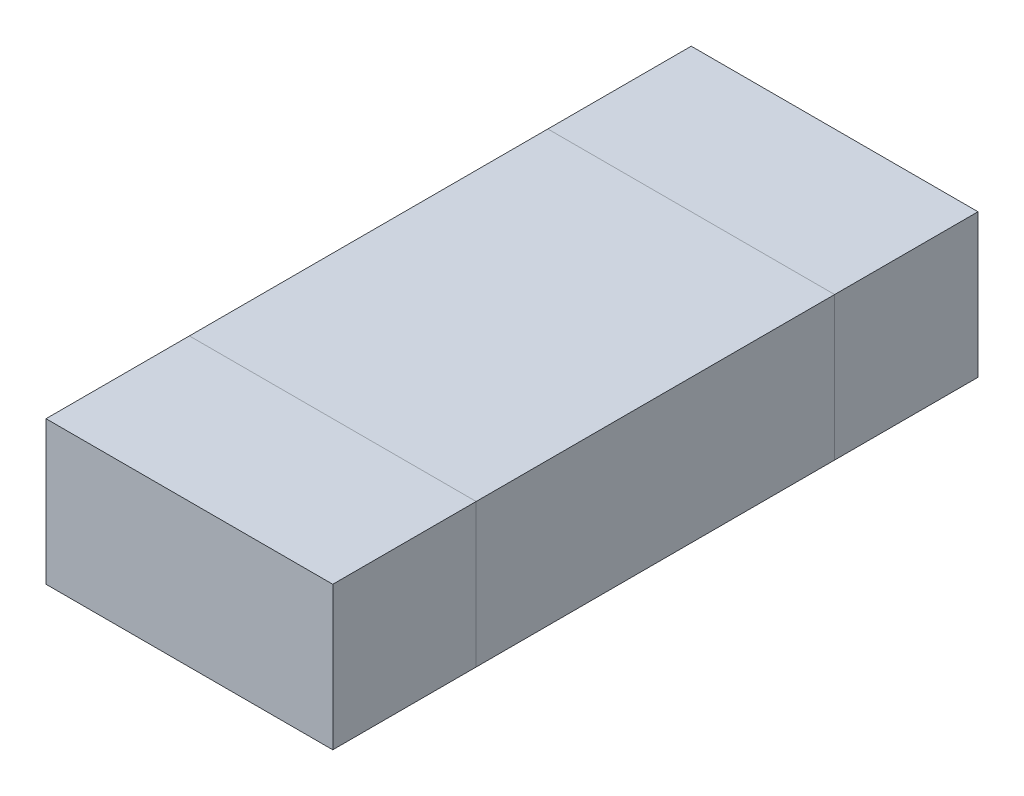
SolidWorks part; units mm, degrees
ref_plane "Front Plane" through (0, 0, 0) normal (0, 0, 1) x (1, 0, 0)
ref_plane "Top Plane" through (0, 0, 0) normal (0, 1, 0) x (1, 0, 0)
ref_plane "Right Plane" through (0, 0, 0) normal (1, 0, 0) x (0, 0, -1)
sketch "MainBodyS" plane through (0, 0, 0) normal (0, 1, 0) x (1, 0, 0)
  line L1 (-0.4, 0.5) -> (0.4, 0.5)
  line L2 (-0.4, 0.5) -> (-0.4, -0.5)
  line L3 (-0.4, -0.5) -> (0.4, -0.5)
  line L4 (0.4, 0.5) -> (0.4, -0.5)
  line L5 (-0.4, 0.5) -> (0.4, -0.5) construction
  line L6 (-0.4, -0.5) -> (0.4, 0.5) construction
  point P0 (0, 0)
  dimension "Length" = 1
  dimension "Width" = 0.8
extrude "MainBody" add sketch "MainBodyS" along normal blind 0.4
sketch "LeftBodyS" plane through (0, 0, 0) normal (0, -1, 0) x (-1, 0, 0)
  line L1 (0.4, -0.5) -> (-0.4, -0.5)
  line L2 (0.4, -0.5) -> (0.4, -0.9)
  line L3 (0.4, -0.9) -> (-0.4, -0.9)
  line L4 (-0.4, -0.5) -> (-0.4, -0.9)
  point P5 (-0.4, -0.5)
  dimension "Width" = 0.4
extrude "Boss-Extrude1" add sketch "LeftBodyS" against normal up to surface (0.4 mm away) separate body up to face at (0, 0.4, 0)
sketch "RightBodyS" plane through (0, 0, 0) normal (0, -1, 0) x (1, 0, 0)
  line L0 (0.4, 0.5) -> (0.4, 0.9) construction
  line L1 (-0.4, -0.5) -> (0.4, -0.5)
  line L2 (-0.4, -0.5) -> (-0.4, -0.9)
  line L3 (-0.4, -0.9) -> (0.4, -0.9)
  line L4 (0.4, -0.5) -> (0.4, -0.9)
  point P5 (0.4, -0.5)
extrude "Boss-Extrude2" add sketch "RightBodyS" against normal up to surface (0.4 mm away) separate body up to face at (0, 0.4, 0)
